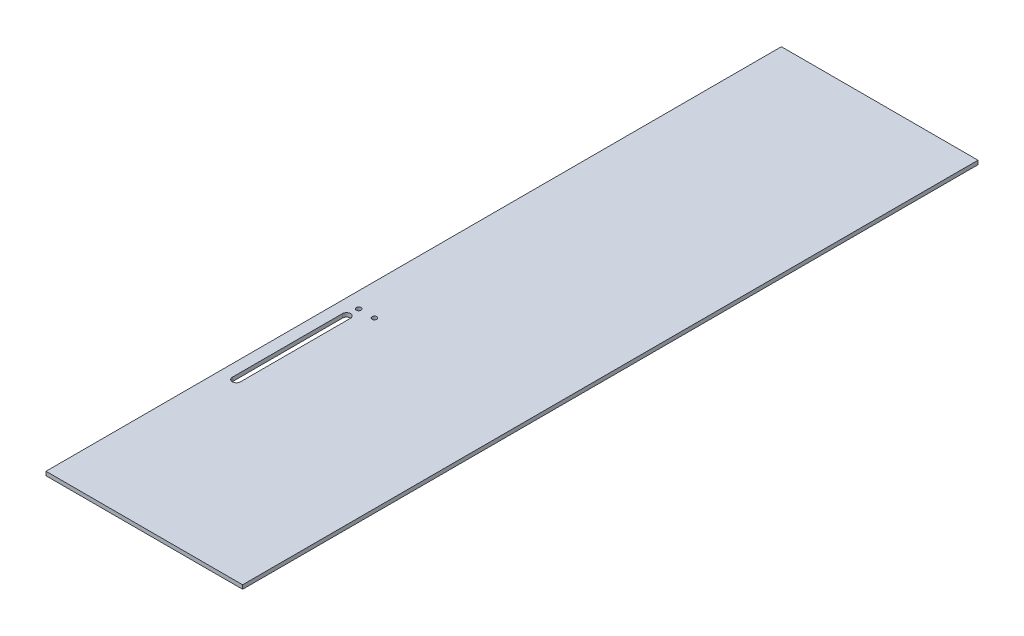
SolidWorks part; units mm, degrees
material "Acrylic (Medium-high impact)"
ref_plane "Front Plane" through (0, 0, 0) normal (0, 0, 1) x (1, 0, 0)
ref_plane "Top Plane" through (0, 0, 0) normal (0, 1, 0) x (1, 0, 0)
ref_plane "Right Plane" through (0, 0, 0) normal (1, 0, 0) x (0, 0, -1)
sketch "Sketch1" plane through (0, 0, 0) normal (0, 1, 0) x (1, 0, 0)
  line L1 (-79.375, -296.8625) -> (79.375, -296.8625)
  line L2 (-79.375, -296.8625) -> (-79.375, 296.8625)
  line L3 (-79.375, 296.8625) -> (79.375, 296.8625)
  line L4 (79.375, -296.8625) -> (79.375, 296.8625)
  line L5 (-79.375, -296.8625) -> (79.375, 296.8625) construction
  line L6 (-79.375, 296.8625) -> (79.375, -296.8625) construction
  point P0 (0, 0)
  dimension "D1" = 158.75
  dimension "D2" = 593.725
extrude "Boss-Extrude1" add sketch "Sketch1" along normal blind 3.175
sketch "Sketch2" [suppressed] plane through (0, 0, 0) normal (0, -1, 0) x (1, 0, 0)
  point P0 (-38.1, -12.7)
  point P1 (-38.1, -44.45)
  point P3 (38.1, -12.7)
  point P5 (38.1, -44.45)
hole_wizard "#10 Clearance Hole1" [suppressed] positions "Sketch3" profile "Sketch5" hole size "#10" standard "ANSI Inch"
sketch "Sketch3" plane through (0, 0, 0) normal (0, -1, 0) x (-1, 0, 0)
  point P0 (38.1, 12.7)
  point P3 (38.1, 44.45)
  point P6 (-38.1, 12.7)
  point P9 (-38.1, 44.45)
sketch "Sketch5" plane through (-38.1, 0, -12.7) normal (1, 0, 0) x (0, 0, -1)
  line L0 (0, 0) -> (0, 3.175)
  line L1 (0, 3.175) -> (2.5527, 3.175)
  line L2 (2.5527, 3.175) -> (2.5527, 0)
  line L5 (2.5527, 0) -> (0, 0)
  line L11 (0, -6.35) -> (0, 107.95) construction
  dimension "Thru Hole Dia." = 5.1054
  dimension "Thru Hole Depth" = 3.175
sketch "Sketch6" [suppressed] plane through (0, -3.175, 0) normal (0, -1, 0) x (-1, 0, 0)
  line L0 (-17.4625, 4.7625) -> (17.4625, 4.7625) construction
  line L1 (23.9395, 52.3875) -> (-23.9395, 52.3875)
  line L2 (23.9395, 52.3875) -> (23.9395, 4.7625)
  line L3 (23.9395, 4.7625) -> (-23.9395, 4.7625)
  line L4 (-23.9395, 52.3875) -> (-23.9395, 4.7625)
  line L5 (23.9395, 52.3875) -> (-23.9395, 4.7625) construction
  line L6 (23.9395, 4.7625) -> (-23.9395, 52.3875) construction
  line L7 (-23.9395, 46.1645) -> (-23.9395, 10.9855) construction
  point P0 (0, 28.575)
extrude "Cut-Extrude1" [suppressed] cut sketch "Sketch6" against normal through all
sketch "Sketch7" plane through (0, 3.175, 0) normal (0, 1, 0) x (1, 0, 0)
  point P0 (-66.675, -57.0992)
  point P1 (-53.975, -57.0992)
  point P3 (-66.675, -66.9417)
hole_wizard "#6 Clearance Hole1" positions "Sketch8" profile "Sketch9" hole size "#6" standard "ANSI Inch"
sketch "Sketch8" plane through (0, 3.175, 0) normal (0, 1, 0) x (1, 0, 0)
  point P11 (-66.675, -57.0992)
  point P14 (-53.975, -57.0992)
  point P18 (0, 0)
  point P19 (0, 0)
sketch "Sketch9" plane through (-66.675, 3.175, 57.0992) normal (1, 0, 0) x (0, 0, 1)
  line L0 (0, 0) -> (0, 13.8408)
  line L1 (0, 13.8408) -> (1.8986, 12.7)
  line L2 (1.8986, 12.7) -> (1.8986, 0)
  line L5 (1.8986, 0) -> (0, 0)
  line L10 (0, 13.8408) -> (-1.8987, 12.7) construction
  line L11 (0, -6.35) -> (0, 107.95) construction
  dimension "Hole Dia." = 3.7973
  dimension "Hole Depth" = 12.7
  dimension "Drill Angle" = 118
sketch "Sketch10" [suppressed] plane through (0, 0, 0) normal (0, -1, 0) x (1, 0, 0)
  point P0 (-172.72, 4.7625)
  point P1 (-172.72, -4.7625)
hole_wizard "1/4 Clearance Hole2" [suppressed] positions "Sketch11" profile "Sketch13" hole size "1/4" standard "ANSI Inch"
sketch "Sketch11" plane through (0, 0, 0) normal (0, -1, 0) x (-1, 0, 0)
  point P0 (182.88, -4.7625)
  point P3 (182.88, 4.7625)
sketch "Sketch13" plane through (-182.88, 0, 4.7625) normal (1, 0, 0) x (0, 0, -1)
  line L0 (0, 0) -> (0, 3.175)
  line L1 (0, 3.175) -> (3.3782, 3.175)
  line L2 (3.3782, 3.175) -> (3.3782, 0)
  line L5 (3.3782, 0) -> (0, 0)
  line L11 (0, -6.35) -> (0, 107.95) construction
  dimension "Thru Hole Dia." = 6.7564
  dimension "Thru Hole Depth" = 3.175
sketch "Sketch14" [suppressed] plane through (0, 0, 0) normal (0, -1, 0) x (1, 0, 0)
  line L0 (-174.625, 0) -> (-187.325, 0) construction
  line L1 (-187.325, 9.525) -> (-187.325, -9.525) construction
  line L2 (-174.625, -3.2639) -> (-187.325, -3.2639)
  line L3 (-174.625, 3.2639) -> (-187.325, 3.2639)
  arc A0 (-174.625, -3.2639) -> (-174.625, 3.2639) centre (-174.625, 0) ccw
  arc A1 (-187.325, 3.2639) -> (-187.325, -3.2639) centre (-187.325, 0) ccw
  point P5 (-180.975, 0)
  dimension "D1" = 6.5278
extrude "Cut-Extrude2" [suppressed] cut sketch "Sketch14" against normal through all
sketch "Sketch15" plane through (0, 3.175, 0) normal (0, 1, 0) x (1, 0, 0)
  line L0 (-66.675, -66.9417) -> (-66.675, -155.8417) construction
  line L1 (-63.4111, -66.9417) -> (-63.4111, -155.8417)
  line L2 (-69.9389, -66.9417) -> (-69.9389, -155.8417)
  arc A0 (-63.4111, -66.9417) -> (-69.9389, -66.9417) centre (-66.675, -66.9417) ccw
  arc A1 (-69.9389, -155.8417) -> (-63.4111, -155.8417) centre (-66.675, -155.8417) ccw
  point P3 (-66.675, -111.3917)
  dimension "D1" = 88.9
  dimension "D2" = 6.5278
extrude "Cut-Extrude3" cut sketch "Sketch15" against normal through all
